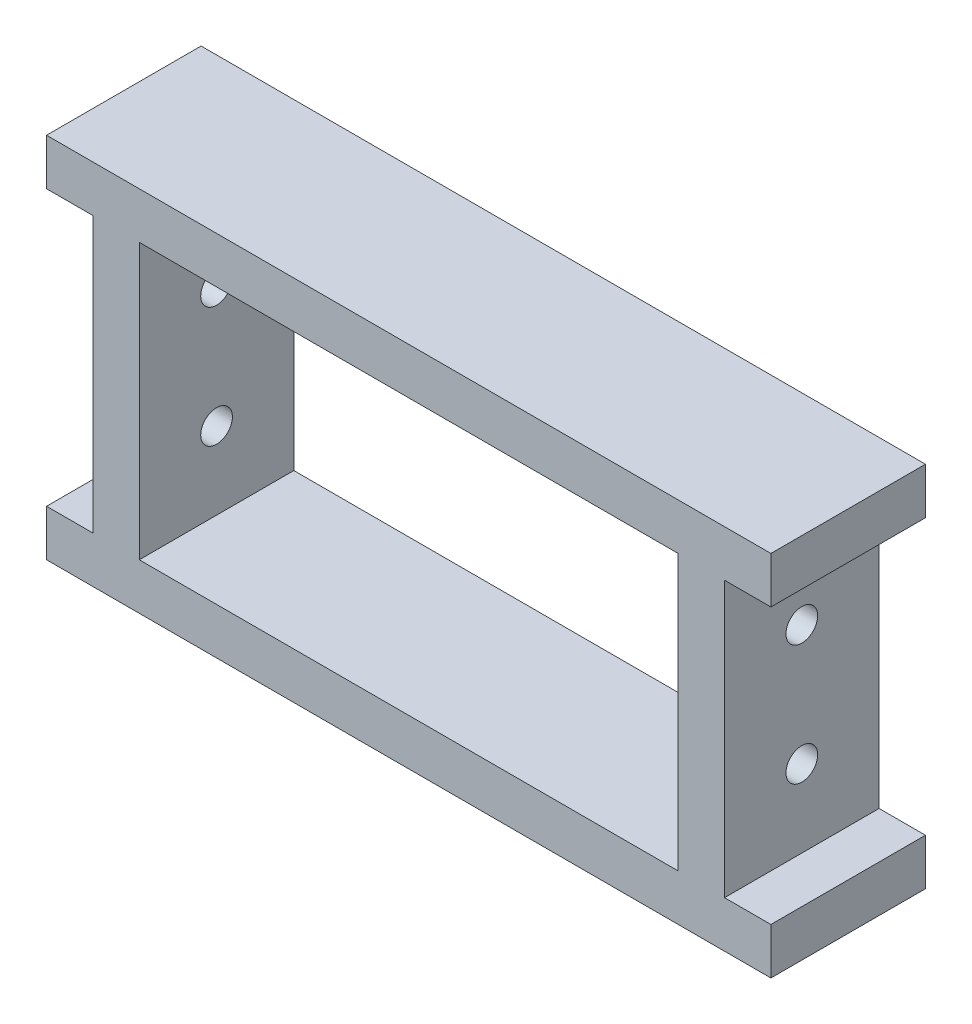
SolidWorks part; units mm, degrees
material "1060 Alloy"
ref_plane "Front Plane" through (0, 0, 0) normal (0, 0, 1) x (1, 0, 0)
ref_plane "Top Plane" through (0, 0, 0) normal (0, 1, 0) x (1, 0, 0)
ref_plane "Right Plane" through (0, 0, 0) normal (1, 0, 0) x (0, 0, -1)
sketch "Sketch1" plane through (0, 0, 0) normal (0, 0, 1) x (1, 0, 0)
  line L0 (6.1496, 9.552) -> (9.1496, 9.552)
  line L1 (-37.7183, 12.552) -> (9.1496, 12.552)
  line L2 (-37.7183, 12.552) -> (-37.7183, 9.552)
  line L3 (9.1496, 9.552) -> (9.1496, 12.552)
  line L4 (-34.7183, 9.552) -> (-34.7183, -8.238)
  line L5 (-31.7183, 9.552) -> (-31.7183, -8.238)
  line L6 (-37.7183, -8.238) -> (-37.7183, -11.238)
  line L7 (-37.7183, -11.238) -> (9.1496, -11.238)
  line L8 (6.1496, 9.552) -> (6.1496, -8.238)
  line L9 (-31.7183, -8.238) -> (3.1496, -8.238)
  line L10 (9.1496, -8.238) -> (9.1496, -11.238)
  line L11 (9.1496, -8.238) -> (6.1496, -8.238)
  line L12 (3.1496, 9.552) -> (3.1496, -8.238)
  line L13 (-31.7183, 9.552) -> (3.1496, 9.552)
  line L15 (-37.7183, 9.552) -> (-34.7183, 9.552)
  line L21 (-37.7183, -8.238) -> (-34.7183, -8.238)
  dimension "D1" = 3
  dimension "D2" = 3
  dimension "D4" = 3
  dimension "D5" = 3
extrude "Boss-Extrude1" add sketch "Sketch1" along normal blind 10
hole_wizard "M2.5x0.45 Tapped Hole2" positions "Sketch4" profile "Sketch5" tap size "M2.5x0.45" standard "Ansi Metric"
sketch "Sketch4" plane through (-34.7183, 0, 0) normal (-1, 0, 0) x (0, 0, 1)
  line L0 (10, 12.552) -> (0, 12.552) construction
  line L2 (0, 9.552) -> (0, -8.238) construction
  line L3 (10, -11.238) -> (0, -11.238) construction
  point P0 (5, 4.552)
  point P1 (5, -3.238)
  dimension "D1" = 8
  dimension "D2" = 8
  dimension "D3" = 5
  dimension "D4" = 5
sketch "Sketch5" plane through (-34.7183, 4.552, 5) normal (0, 1, 0) x (0, 0, 1)
  line L0 (0, 0) -> (0, 7.8659)
  line L1 (0, 7.8659) -> (1.025, 7.25)
  line L2 (1.025, 7.25) -> (1.025, 0)
  line L5 (1.025, 0) -> (0, 0)
  line L10 (0, 7.8659) -> (-1.025, 7.25) construction
  line L11 (0, -6.35) -> (0, 107.95) construction
  dimension "Tap Drill Dia." = 2.05
  dimension "Tap Drill Depth" = 7.25
  dimension "Drill Angle" = 118
cosmetic thread "Hole Thread1" parameters "D1"=3, "D2"=2.5
cosmetic thread "Hole Thread2" parameters "D1"=3, "D2"=2.5
hole_wizard "M2.5x0.45 Tapped Hole1" positions "Sketch7" profile "Sketch6" tap size "M2.5x0.45" standard "Ansi Metric"
sketch "Sketch7" plane through (6.1496, 2.4767, 1.6069) normal (1, 0, 0) x (0, 0, -1)
  line L3 (-8.3931, 10.0753) -> (1.6069, 10.0753) construction
  line L4 (-8.3931, -13.7147) -> (1.6069, -13.7147) construction
  line L5 (-8.3931, 7.0753) -> (-8.3931, 10.0753) construction
  line L6 (-8.3931, -13.7147) -> (-8.3931, -10.7147) construction
  point P0 (-3.3931, 2.0753)
  point P1 (-3.3931, -5.7147)
  dimension "D1" = 8
  dimension "D2" = 8
  dimension "D3" = 5
  dimension "D4" = 5
sketch "Sketch6" plane through (6.1496, 4.552, 5) normal (0, 1, 0) x (0, 0, -1)
  line L0 (0, 0) -> (0, 7.8659)
  line L1 (0, 7.8659) -> (1.025, 7.25)
  line L2 (1.025, 7.25) -> (1.025, 0)
  line L5 (1.025, 0) -> (0, 0)
  line L10 (0, 7.8659) -> (-1.025, 7.25) construction
  line L11 (0, -6.35) -> (0, 107.95) construction
  dimension "Tap Drill Dia." = 2.05
  dimension "Tap Drill Depth" = 7.25
  dimension "Drill Angle" = 118
cosmetic thread "Hole Thread3" parameters "D1"=3, "D2"=2.5
cosmetic thread "Hole Thread4" parameters "D1"=3, "D2"=2.5
